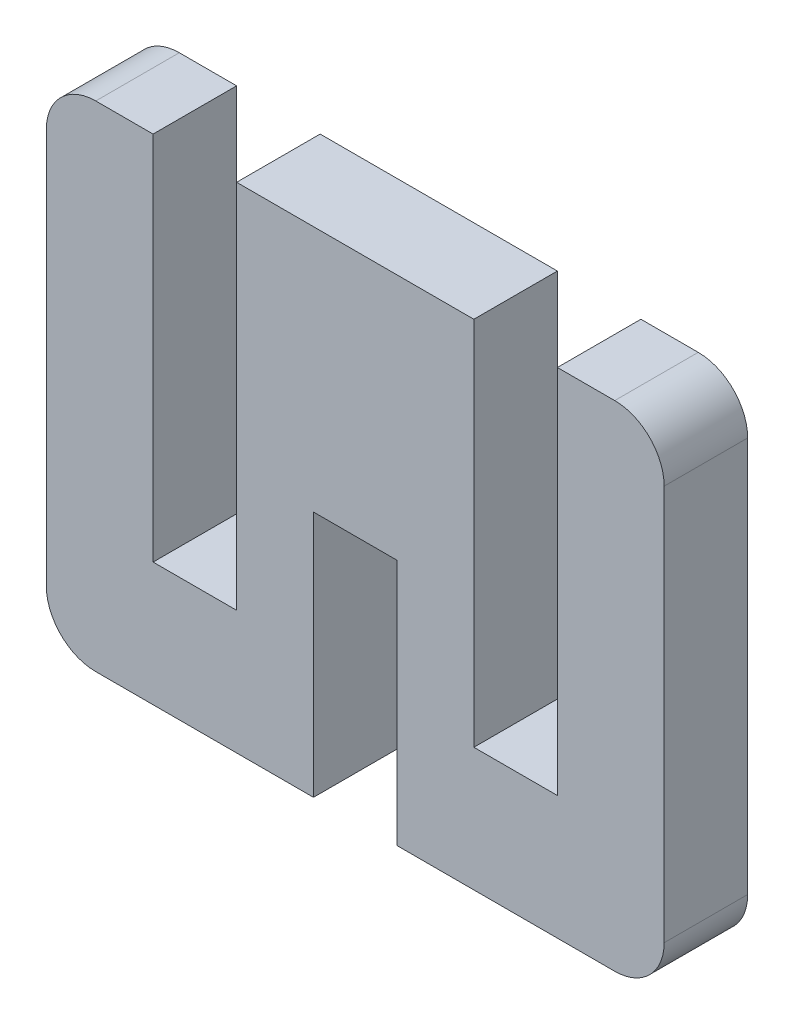
SolidWorks part; units mm, degrees
ref_plane "Front Plane" through (0, 0, 0) normal (0, 0, 1) x (1, 0, 0)
ref_plane "Top Plane" through (0, 0, 0) normal (0, 1, 0) x (1, 0, 0)
ref_plane "Right Plane" through (0, 0, 0) normal (1, 0, 0) x (0, 0, -1)
sketch "Sketch1" plane through (0, 0, 0) normal (0, 0, 1) x (1, 0, 0)
  line L1 (-15.875, -12.7) -> (15.875, -12.7)
  line L2 (-15.875, -12.7) -> (-15.875, 12.7)
  line L3 (-15.875, 12.7) -> (15.875, 12.7)
  line L4 (15.875, -12.7) -> (15.875, 12.7)
  line L5 (-15.875, -12.7) -> (15.875, 12.7) construction
  line L6 (-15.875, 12.7) -> (15.875, -12.7) construction
  point P0 (0, 0)
  dimension "D1" = 25.4
  dimension "D2" = 31.75
extrude "Boss-Extrude1" add sketch "Sketch1" along normal blind 4.2926
fillet "Fillet1" radius 2.54 4 edges at (-15.875, -12.7, 2.1463) (15.875, -12.7, 2.1463) (15.875, 12.7, 2.1463) (-15.875, 12.7, 2.1463)
sketch "Sketch2" plane through (0, 0, 4.2926) normal (0, 0, 1) x (1, 0, 0)
  line L5 (13.335, 12.7) -> (-13.335, 12.7) construction
  line L6 (-13.335, -12.7) -> (13.335, -12.7) construction
  line L7 (-10.3886, 12.7) -> (-6.096, 12.7)
  line L8 (-10.3886, 12.7) -> (-10.3886, -6.35)
  line L9 (-10.3886, -6.35) -> (-6.096, -6.35)
  line L10 (-6.096, 12.7) -> (-6.096, -6.35)
  line L11 (-10.3886, 12.7) -> (-6.096, -6.35) construction
  line L12 (-10.3886, -6.35) -> (-6.096, 12.7) construction
  line L13 (6.096, 12.7) -> (10.3886, 12.7)
  line L14 (6.096, 12.7) -> (6.096, -6.35)
  line L15 (6.096, -6.35) -> (10.3886, -6.35)
  line L16 (10.3886, 12.7) -> (10.3886, -6.35)
  line L17 (6.096, 12.7) -> (10.3886, -6.35) construction
  line L18 (6.096, -6.35) -> (10.3886, 12.7) construction
  line L19 (-8.2423, 3.175) -> (8.2423, 3.175)
  line L20 (-2.1463, -12.7) -> (2.1463, -12.7)
  line L21 (-2.1463, -12.7) -> (-2.1463, 0)
  line L22 (-2.1463, 0) -> (2.1463, 0)
  line L23 (2.1463, -12.7) -> (2.1463, 0)
  line L24 (-2.1463, -12.7) -> (2.1463, 0) construction
  line L25 (-2.1463, 0) -> (2.1463, -12.7) construction
  point P0 (0, 3.175)
  point P4 (0, -6.35)
  point P5 (-8.2423, 3.175)
  point P11 (8.2423, 3.175)
  dimension "D1" = 4.2926
  dimension "D2" = 4.2926
  dimension "D5" = 12.192
  dimension "D3" = 19.05
  dimension "D4" = 4.2926
  dimension "D6" = 12.7
extrude "Cut-Extrude2" cut sketch "Sketch2" against normal blind 4.2926
equation "\"thick\"=0.169"
equation "\"D1@Boss-Extrude1\"=\"thick\""
equation "\"D1@Sketch2\"=\"thick\""
equation "\"D2@Sketch2\"=\"thick\""
equation "\"2thick\"=0.305913"
equation "\"2xthick\"=0.338"
equation "\"D4@Sketch2\"=\"thick\""
